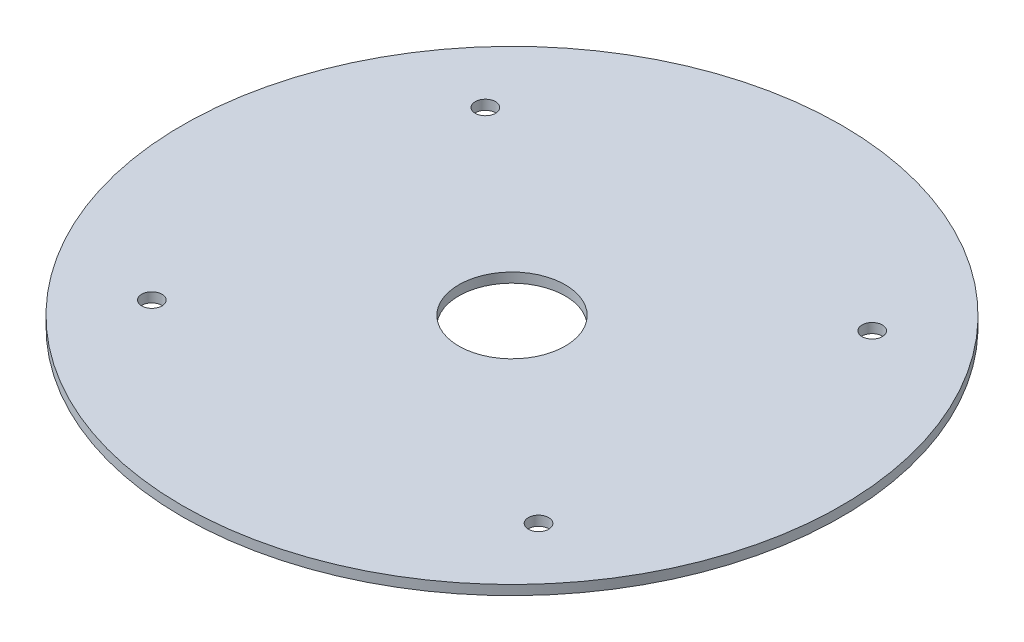
SolidWorks part; units mm, degrees
ref_plane "Front Plane" through (0, 0, 0) normal (0, 0, 1) x (1, 0, 0)
ref_plane "Top Plane" through (0, 0, 0) normal (0, 1, 0) x (1, 0, 0)
ref_plane "Right Plane" through (0, 0, 0) normal (1, 0, 0) x (0, 0, -1)
sketch "Sketch1" plane through (0, 0, 0) normal (0, 1, 0) x (1, 0, 0)
  circle A1 centre (-33.2088, 42.5652) radius 2.1
  circle A2 centre (46.7916, 42.5652) radius 2.1
  circle A3 centre (-33.2088, -26.4348) radius 2.1
  circle A4 centre (46.796, -26.4508) radius 2.1
  circle A5 centre (6.7914, 8.0652) radius 68.169
  circle A6 centre (6.7914, 8.0652) radius 11
  point P1 (0, 0)
  point P2 (0, 0)
  point P7 (0, 0)
  dimension "D1" = 22
  dimension "D2" = 4.2
  dimension "D3" = 80.0005
  dimension "D4" = 69.016
extrude "Boss-Extrude1" add sketch "Sketch1" along normal blind 2
